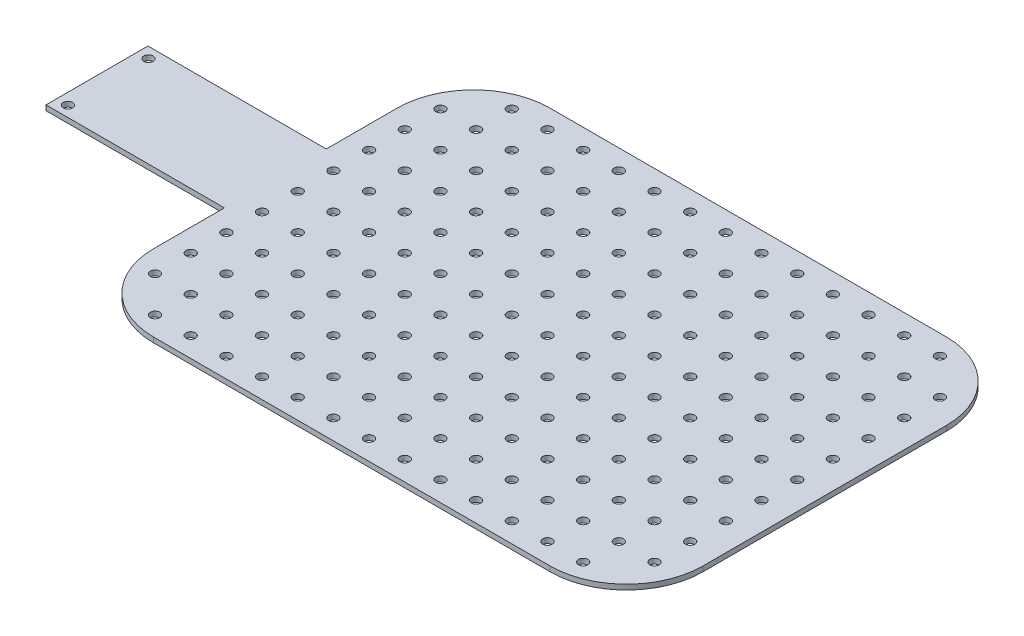
SolidWorks part; units mm, degrees
ref_plane "Front Plane" through (0, 0, 0) normal (0, 0, 1) x (1, 0, 0)
ref_plane "Top Plane" through (0, 0, 0) normal (0, 1, 0) x (1, 0, 0)
ref_plane "Right Plane" through (0, 0, 0) normal (1, 0, 0) x (0, 0, -1)
sketch "Sketch1" plane through (0, 0, 0) normal (0, 1, 0) x (1, 0, 0)
  line L0 (0, 0) -> (0, 155.575) construction
  line L1 (77.8, 155.575) -> (-77.8, 155.575)
  line L2 (-107.8, 125.575) -> (-107.8, 97.7875)
  line L3 (-107.8, 97.7875) -> (-177.8, 97.7875)
  line L4 (-177.8, 97.7875) -> (-177.8, 57.7875)
  line L5 (-177.8, 57.7875) -> (-107.8, 57.7875)
  line L6 (-107.8, 57.7875) -> (-107.8, 30)
  line L7 (-77.8, 0) -> (77.8, 0)
  line L8 (-173.4, 93.5875) -> (-173.4, 61.9875) construction
  line L9 (-177.8, 77.7875) -> (-107.8, 77.7875) construction
  line L10 (173.4, 93.5875) -> (173.4, 61.9875) construction
  line L11 (107.8, 57.7875) -> (107.8, 30)
  line L12 (177.8, 57.7875) -> (107.8, 57.7875)
  line L13 (177.8, 97.7875) -> (177.8, 57.7875)
  line L14 (107.8, 97.7875) -> (177.8, 97.7875)
  line L15 (107.8, 125.575) -> (107.8, 97.7875)
  circle A0 centre (-173.4, 93.5875) radius 1.85
  circle A1 centre (-173.4, 61.9875) radius 1.85
  circle A2 centre (173.4, 61.9875) radius 1.85
  circle A3 centre (173.4, 93.5875) radius 1.85
  arc A4 (107.8, 30) -> (77.8, 0) centre (77.8, 30) cw
  arc A5 (-107.8, 30) -> (-77.8, 0) centre (-77.8, 30) ccw
  arc A6 (107.8, 125.575) -> (77.8, 155.575) centre (77.8, 125.575) ccw
  arc A7 (-77.8, 155.575) -> (-107.8, 125.575) centre (-77.8, 125.575) ccw
  point P15 (-173.4, 77.7875)
  point P29 (107.8, 0)
  point P32 (-107.8, 0)
  point P35 (107.8, 155.575)
  point P38 (-107.8, 155.575)
  dimension "D5" = 3.7
  dimension "D8" = 30
  dimension "D1" = 155.575
  dimension "D2" = 177.8
  dimension "D3" = 40
  dimension "D4" = 31.6
  dimension "D6" = 4.4
  dimension "D7" = 70
extrude "Boss-Extrude1" add sketch "Sketch1" along normal blind 2
sketch "Sketch2" plane through (0, 2, 0) normal (0, 1, 0) x (1, 0, 0)
  line L0 (-99.0132, 8.7868) -> (-99.0132, 146.7882) construction
  line L1 (-99.0132, 146.7882) -> (99.0132, 146.7882) construction
  line L2 (99.0132, 146.7882) -> (99.0132, 8.7868) construction
  line L3 (99.0132, 8.7868) -> (-99.0132, 8.7868) construction
  line L4 (-177.8, 77.7875) -> (177.8, 77.7875) construction
  line L5 (-177.8, 97.7875) -> (-177.8, 57.7875) construction
  line L6 (177.8, 57.7875) -> (177.8, 97.7875) construction
  arc A0 (-107.8, 30) -> (-77.8, 0) centre (-77.8, 30) ccw construction
  arc A1 (-77.8, 155.575) -> (-107.8, 125.575) centre (-77.8, 125.575) ccw construction
  arc A2 (107.8, 125.575) -> (77.8, 155.575) centre (77.8, 125.575) ccw construction
  arc A3 (77.8, 0) -> (107.8, 30) centre (77.8, 30) ccw construction
  circle A4 centre (-99.0132, 21.7875) radius 1.85
  circle A5 centre (-99.0132, 35.7875) radius 1.85
  circle A6 centre (-99.0132, 49.7875) radius 1.85
  circle A7 centre (-99.0132, 63.7875) radius 1.85
  circle A8 centre (-99.0132, 77.7875) radius 1.85
  circle A9 centre (-99.0132, 91.7875) radius 1.85
  circle A10 centre (-99.0132, 105.7875) radius 1.85
  circle A11 centre (-99.0132, 119.7875) radius 1.85
  circle A12 centre (-99.0132, 133.7875) radius 1.85
  circle A13 centre (-85.0132, 63.7875) radius 1.85
  circle A14 centre (-85.0132, 49.7875) radius 1.85
  circle A15 centre (-85.0132, 35.7875) radius 1.85
  circle A16 centre (-85.0132, 21.7875) radius 1.85
  circle A17 centre (-85.0132, 91.7875) radius 1.85
  circle A18 centre (-85.0132, 105.7875) radius 1.85
  circle A19 centre (-85.0132, 77.7875) radius 1.85
  circle A20 centre (-85.0132, 133.7875) radius 1.85
  circle A21 centre (-85.0132, 119.7875) radius 1.85
  circle A22 centre (-71.0132, 63.7875) radius 1.85
  circle A23 centre (-71.0132, 49.7875) radius 1.85
  circle A24 centre (-71.0132, 35.7875) radius 1.85
  circle A25 centre (-71.0132, 21.7875) radius 1.85
  circle A26 centre (-71.0132, 91.7875) radius 1.85
  circle A27 centre (-71.0132, 105.7875) radius 1.85
  circle A28 centre (-71.0132, 77.7875) radius 1.85
  circle A29 centre (-71.0132, 133.7875) radius 1.85
  circle A30 centre (-71.0132, 119.7875) radius 1.85
  circle A31 centre (-57.0132, 63.7875) radius 1.85
  circle A32 centre (-57.0132, 49.7875) radius 1.85
  circle A33 centre (-57.0132, 35.7875) radius 1.85
  circle A34 centre (-57.0132, 21.7875) radius 1.85
  circle A35 centre (-57.0132, 91.7875) radius 1.85
  circle A36 centre (-57.0132, 105.7875) radius 1.85
  circle A37 centre (-57.0132, 77.7875) radius 1.85
  circle A38 centre (-57.0132, 133.7875) radius 1.85
  circle A39 centre (-57.0132, 119.7875) radius 1.85
  circle A40 centre (-43.0132, 63.7875) radius 1.85
  circle A41 centre (-43.0132, 49.7875) radius 1.85
  circle A42 centre (-43.0132, 35.7875) radius 1.85
  circle A43 centre (-43.0132, 21.7875) radius 1.85
  circle A44 centre (-43.0132, 91.7875) radius 1.85
  circle A45 centre (-43.0132, 105.7875) radius 1.85
  circle A46 centre (-43.0132, 77.7875) radius 1.85
  circle A47 centre (-43.0132, 133.7875) radius 1.85
  circle A48 centre (-43.0132, 119.7875) radius 1.85
  circle A49 centre (-29.0132, 63.7875) radius 1.85
  circle A50 centre (-29.0132, 49.7875) radius 1.85
  circle A51 centre (-29.0132, 35.7875) radius 1.85
  circle A52 centre (-29.0132, 21.7875) radius 1.85
  circle A53 centre (-29.0132, 91.7875) radius 1.85
  circle A54 centre (-29.0132, 105.7875) radius 1.85
  circle A55 centre (-29.0132, 77.7875) radius 1.85
  circle A56 centre (-29.0132, 133.7875) radius 1.85
  circle A57 centre (-29.0132, 119.7875) radius 1.85
  circle A58 centre (-15.0132, 63.7875) radius 1.85
  circle A59 centre (-15.0132, 49.7875) radius 1.85
  circle A60 centre (-15.0132, 35.7875) radius 1.85
  circle A61 centre (-15.0132, 21.7875) radius 1.85
  circle A62 centre (-15.0132, 91.7875) radius 1.85
  circle A63 centre (-15.0132, 105.7875) radius 1.85
  circle A64 centre (-15.0132, 77.7875) radius 1.85
  circle A65 centre (-15.0132, 133.7875) radius 1.85
  circle A66 centre (-15.0132, 119.7875) radius 1.85
  circle A67 centre (-1.0132, 63.7875) radius 1.85
  circle A68 centre (-1.0132, 49.7875) radius 1.85
  circle A69 centre (-1.0132, 35.7875) radius 1.85
  circle A70 centre (-1.0132, 21.7875) radius 1.85
  circle A71 centre (-1.0132, 91.7875) radius 1.85
  circle A72 centre (-1.0132, 105.7875) radius 1.85
  circle A73 centre (-1.0132, 77.7875) radius 1.85
  circle A74 centre (-1.0132, 133.7875) radius 1.85
  circle A75 centre (-1.0132, 119.7875) radius 1.85
  circle A76 centre (12.9868, 63.7875) radius 1.85
  circle A77 centre (12.9868, 49.7875) radius 1.85
  circle A78 centre (12.9868, 35.7875) radius 1.85
  circle A79 centre (12.9868, 21.7875) radius 1.85
  circle A80 centre (12.9868, 91.7875) radius 1.85
  circle A81 centre (12.9868, 105.7875) radius 1.85
  circle A82 centre (12.9868, 77.7875) radius 1.85
  circle A83 centre (12.9868, 133.7875) radius 1.85
  circle A84 centre (12.9868, 119.7875) radius 1.85
  circle A85 centre (26.9868, 63.7875) radius 1.85
  circle A86 centre (26.9868, 49.7875) radius 1.85
  circle A87 centre (26.9868, 35.7875) radius 1.85
  circle A88 centre (26.9868, 21.7875) radius 1.85
  circle A89 centre (26.9868, 91.7875) radius 1.85
  circle A90 centre (26.9868, 105.7875) radius 1.85
  circle A91 centre (26.9868, 77.7875) radius 1.85
  circle A92 centre (26.9868, 133.7875) radius 1.85
  circle A93 centre (26.9868, 119.7875) radius 1.85
  circle A94 centre (40.9868, 63.7875) radius 1.85
  circle A95 centre (40.9868, 49.7875) radius 1.85
  circle A96 centre (40.9868, 35.7875) radius 1.85
  circle A97 centre (40.9868, 21.7875) radius 1.85
  circle A98 centre (40.9868, 91.7875) radius 1.85
  circle A99 centre (40.9868, 105.7875) radius 1.85
  circle A100 centre (40.9868, 77.7875) radius 1.85
  circle A101 centre (40.9868, 133.7875) radius 1.85
  circle A102 centre (40.9868, 119.7875) radius 1.85
  circle A103 centre (54.9868, 63.7875) radius 1.85
  circle A104 centre (54.9868, 49.7875) radius 1.85
  circle A105 centre (54.9868, 35.7875) radius 1.85
  circle A106 centre (54.9868, 21.7875) radius 1.85
  circle A107 centre (54.9868, 91.7875) radius 1.85
  circle A108 centre (54.9868, 105.7875) radius 1.85
  circle A109 centre (54.9868, 77.7875) radius 1.85
  circle A110 centre (54.9868, 133.7875) radius 1.85
  circle A111 centre (54.9868, 119.7875) radius 1.85
  circle A112 centre (68.9868, 63.7875) radius 1.85
  circle A113 centre (68.9868, 49.7875) radius 1.85
  circle A114 centre (68.9868, 35.7875) radius 1.85
  circle A115 centre (68.9868, 21.7875) radius 1.85
  circle A116 centre (68.9868, 91.7875) radius 1.85
  circle A117 centre (68.9868, 105.7875) radius 1.85
  circle A118 centre (68.9868, 77.7875) radius 1.85
  circle A119 centre (68.9868, 133.7875) radius 1.85
  circle A120 centre (68.9868, 119.7875) radius 1.85
  circle A121 centre (82.9868, 63.7875) radius 1.85
  circle A122 centre (82.9868, 49.7875) radius 1.85
  circle A123 centre (82.9868, 35.7875) radius 1.85
  circle A124 centre (82.9868, 21.7875) radius 1.85
  circle A125 centre (82.9868, 91.7875) radius 1.85
  circle A126 centre (82.9868, 105.7875) radius 1.85
  circle A127 centre (82.9868, 77.7875) radius 1.85
  circle A128 centre (82.9868, 133.7875) radius 1.85
  circle A129 centre (82.9868, 119.7875) radius 1.85
  circle A130 centre (96.9868, 63.7875) radius 1.85
  circle A131 centre (96.9868, 49.7875) radius 1.85
  circle A132 centre (96.9868, 35.7875) radius 1.85
  circle A133 centre (96.9868, 21.7875) radius 1.85
  circle A134 centre (96.9868, 91.7875) radius 1.85
  circle A135 centre (96.9868, 105.7875) radius 1.85
  circle A136 centre (96.9868, 77.7875) radius 1.85
  circle A137 centre (96.9868, 133.7875) radius 1.85
  circle A138 centre (96.9868, 119.7875) radius 1.85
  circle A139 centre (-85.0132, 147.7875) radius 1.85
  circle A140 centre (-1.0132, 147.7875) radius 1.85
  circle A141 centre (-15.0132, 147.7875) radius 1.85
  circle A142 centre (-29.0132, 147.7875) radius 1.85
  circle A143 centre (-43.0132, 147.7875) radius 1.85
  circle A144 centre (-57.0132, 147.7875) radius 1.85
  circle A145 centre (-71.0132, 147.7875) radius 1.85
  circle A146 centre (12.9868, 147.7875) radius 1.85
  circle A147 centre (26.9868, 147.7875) radius 1.85
  circle A148 centre (82.9868, 147.7875) radius 1.85
  circle A149 centre (68.9868, 147.7875) radius 1.85
  circle A150 centre (54.9868, 147.7875) radius 1.85
  circle A151 centre (40.9868, 147.7875) radius 1.85
  circle A152 centre (-85.0132, 35.7875) radius 1.85
  circle A153 centre (-85.0132, 7.7875) radius 1.85
  circle A154 centre (-71.0132, 7.7875) radius 1.85
  circle A155 centre (-57.0132, 7.7875) radius 1.85
  circle A156 centre (-43.0132, 7.7875) radius 1.85
  circle A157 centre (-29.0132, 7.7875) radius 1.85
  circle A158 centre (-15.0132, 7.7875) radius 1.85
  circle A159 centre (-1.0132, 7.7875) radius 1.85
  circle A160 centre (12.9868, 7.7875) radius 1.85
  circle A161 centre (26.9868, 7.7875) radius 1.85
  circle A162 centre (40.9868, 7.7875) radius 1.85
  circle A163 centre (54.9868, 7.7875) radius 1.85
  circle A164 centre (68.9868, 7.7875) radius 1.85
  circle A165 centre (82.9868, 7.7875) radius 1.85
  dimension "D1" = 3.7
  dimension "D2" = 9
  dimension "D3" = 15
  dimension "D4" = 2
  dimension "D5" = 2
extrude "Cut-Extrude1" cut sketch "Sketch2" against normal blind 2
sketch "Sketch3" plane through (177.8, 0, 0) normal (1, 0, 0) x (0, 0, -1)
  line L4 (57.7875, 0) -> (97.7875, 0)
  line L5 (97.7875, 0) -> (97.7875, 2)
  line L6 (97.7875, 2) -> (57.7875, 2)
  line L7 (57.7875, 2) -> (57.7875, 0)
  line L8 (57.7875, 0) -> (97.7875, 0)
  line L9 (97.7875, 0) -> (97.7875, 2)
  line L10 (97.7875, 2) -> (57.7875, 2)
  line L11 (57.7875, 2) -> (57.7875, 0)
  dimension "D1" = 0
extrude "Cut-Extrude2" cut sketch "Sketch3" against normal up to surface (70 mm away) up to face at (107.8, 1, -111.6812)
